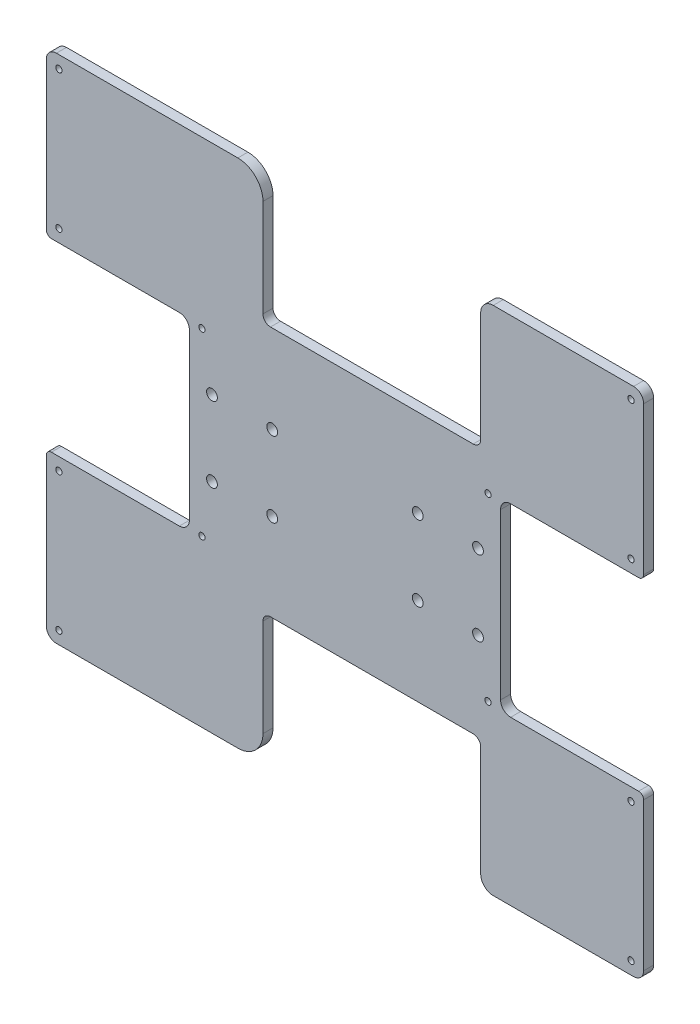
SolidWorks part; units mm, degrees
ref_plane "Front Plane" through (0, 0, 0) normal (0, 0, 1) x (1, 0, 0)
ref_plane "Top Plane" through (0, 0, 0) normal (0, 1, 0) x (1, 0, 0)
ref_plane "Right Plane" through (0, 0, 0) normal (1, 0, 0) x (0, 0, -1)
sketch "Sketch1" plane through (0, 0, 0) normal (0, 0, 1) x (1, 0, 0)
  line L0 (-141.718, 60) -> (-138.7986, 60) construction
  line L1 (-120, -43.5068) -> (-120, -41.8068) construction
  line L3 (-119, 97.8466) -> (-119, 38.8493)
  line L18 (-61.9992, -32.8493) -> (-61.9992, 32.8493)
  line L19 (-65.9992, 36.8493) -> (-117, 36.8493)
  line L20 (-29.6905, -50.0074) -> (51.0771, -50.0074)
  line L21 (-32.6905, -91.8466) -> (-32.6905, -53.0074)
  line L22 (-115, -101.8466) -> (-42.6905, -101.8466)
  line L23 (-65.9992, -36.8493) -> (-117, -36.8493)
  line L30 (-119, -97.8466) -> (-119, -38.8493)
  line L33 (-32.6905, 91.8466) -> (-32.6905, 53.0074)
  line L34 (-29.6905, 50.0074) -> (29.6905, 50.0074)
  line L35 (0, 0) -> (-20, 0) construction
  line L36 (0, 0) -> (0, 19.5721) construction
  line L40 (-115, 101.8466) -> (-42.6905, 101.8466)
  line L41 (115, 101.8466) -> (59.0771, 101.8466)
  line L43 (119, -97.8466) -> (119, -38.8493)
  line L44 (65.9992, -36.8493) -> (117, -36.8493)
  line L45 (115, -101.8466) -> (59.0771, -101.8466)
  line L47 (65.9992, 36.8493) -> (117, 36.8493)
  line L48 (61.9992, -32.8493) -> (61.9992, 32.8493)
  line L49 (119, 97.8466) -> (119, 38.8493)
  line L50 (29.6905, 50.0074) -> (51.0771, 50.0074)
  line L51 (54.0771, 53.0074) -> (54.0771, 96.8466)
  line L56 (54.0771, -53.0074) -> (54.0771, -96.8466)
  arc A3 (-119, 38.8493) -> (-117, 36.8493) centre (-117, 38.8493) ccw
  arc A27 (-32.6905, -53.0074) -> (-29.6905, -50.0074) centre (-29.6905, -53.0074) cw
  arc A31 (-42.6905, -101.8466) -> (-32.6905, -91.8466) centre (-42.6905, -91.8466) ccw
  arc A33 (-61.9992, -32.8493) -> (-65.9992, -36.8493) centre (-65.9992, -32.8493) cw
  arc A45 (-119, -38.8493) -> (-117, -36.8493) centre (-117, -38.8493) cw
  arc A50 (-61.9992, 32.8493) -> (-65.9992, 36.8493) centre (-65.9992, 32.8493) ccw
  arc A65 (-119, -97.8466) -> (-115, -101.8466) centre (-115, -97.8466) ccw
  arc A67 (-119, 97.8466) -> (-115, 101.8466) centre (-115, 97.8466) cw
  circle A71 centre (29, 15) radius 1.5
  circle A73 centre (53, 15) radius 1.5
  circle A75 centre (53, -15) radius 1.5
  circle A77 centre (29, -15) radius 1.5
  arc A82 (119, 97.8466) -> (115, 101.8466) centre (115, 97.8466) ccw
  arc A83 (119, -97.8466) -> (115, -101.8466) centre (115, -97.8466) cw
  arc A84 (61.9992, 32.8493) -> (65.9992, 36.8493) centre (65.9992, 32.8493) cw
  arc A85 (119, -38.8493) -> (117, -36.8493) centre (117, -38.8493) ccw
  arc A86 (61.9992, -32.8493) -> (65.9992, -36.8493) centre (65.9992, -32.8493) ccw
  arc A89 (119, 38.8493) -> (117, 36.8493) centre (117, 38.8493) cw
  arc A91 (51.0771, 50.0074) -> (54.0771, 53.0074) centre (51.0771, 53.0074) ccw
  arc A93 (54.0771, 96.8466) -> (59.0771, 101.8466) centre (59.0771, 96.8466) cw
  arc A95 (-42.6905, 101.8466) -> (-32.6905, 91.8466) centre (-42.6905, 91.8466) cw
  arc A106 (-32.6905, 53.0074) -> (-29.6905, 50.0074) centre (-29.6905, 53.0074) ccw
  arc A107 (51.0771, -50.0074) -> (54.0771, -53.0074) centre (51.0771, -53.0074) cw
  arc A108 (54.0771, -96.8466) -> (59.0771, -101.8466) centre (59.0771, -96.8466) ccw
  circle A109 centre (-114, 41.8493) radius 1
  circle A110 centre (-56.9992, 35.8493) radius 1
  circle A111 centre (-114, 96.8466) radius 1
  circle A112 centre (114, 96.8466) radius 1
  circle A113 centre (56.9992, 35.8493) radius 1
  circle A114 centre (-29, -15) radius 1.5
  circle A115 centre (-53, -15) radius 1.5
  circle A116 centre (-53, 15) radius 1.5
  circle A117 centre (-29, 15) radius 1.5
  circle A118 centre (114, 41.8493) radius 1
  circle A119 centre (114, -96.8466) radius 1
  circle A120 centre (114, -41.8493) radius 1
  circle A121 centre (56.9992, -35.8493) radius 1
  circle A122 centre (-56.9992, -35.8493) radius 1
  circle A123 centre (-114, -96.8466) radius 1
  circle A124 centre (-114, -41.8493) radius 1
  point P4 (0, -50.0074)
  point P7 (0, -50.0074)
  point P8 (61.9992, 0)
  point P65 (0, 50.0074)
  point P83 (0, 50.0074)
  point P111 (-61.9992, 0)
  dimension "D1" = 10
  dimension "D2" = 3
  dimension "D3" = 4
  dimension "D4" = 24
  dimension "D5" = 3
  dimension "D6" = 30
  dimension "D9" = 5
  dimension "D10" = 2
  dimension "D11" = 2
  dimension "D12" = 5
  dimension "D13" = 5
  dimension "D8" = 3
  dimension "D14" = 2
  dimension "D15" = 5
  dimension "D16" = 1
  dimension "D17" = 2
  dimension "D18" = 5
  dimension "D19" = 5
  dimension "D7" = 2
extrude "Boss-Extrude1" add sketch "Sketch1" along normal blind 4
hole_wizard "M4 Clearance Hole1" positions "3DSketch1" profile "Sketch2" hole size "M4" standard "ISO"
sketch3d "3DSketch1"
  line L0 (-53, 15, 4) -> (-53, 15, 0) construction
  line L1 (-29, 15, 4) -> (-29, 15, 0) construction
  line L2 (-53, -15, 4) -> (-53, -15, 0) construction
  line L3 (-29, -15, 4) -> (-29, -15, 0) construction
  line L4 (29, -15, 4) -> (29, -15, 0) construction
  line L5 (53, -15, 4) -> (53, -15, 0) construction
  line L6 (53, 15, 4) -> (53, 15, 0) construction
  line L7 (29, 15, 4) -> (29, 15, 0) construction
  point P0 (-53, 15, 4)
  point P4 (-29, 15, 4)
  point P8 (-53, -15, 4)
  point P12 (-29, -15, 4)
  point P16 (29, -15, 4)
  point P20 (53, -15, 4)
  point P24 (53, 15, 4)
  point P28 (29, 15, 4)
sketch "Sketch2" plane through (-53, 15, 4) normal (1, 0, 0) x (0, -1, 0)
  line L0 (0, 0) -> (0, 7.2919)
  line L1 (0, 7.2919) -> (2.15, 6)
  line L2 (2.15, 6) -> (2.15, 0)
  line L5 (2.15, 0) -> (0, 0)
  line L10 (0, 7.2919) -> (-2.15, 6) construction
  line L11 (0, -6.35) -> (0, 107.95) construction
  dimension "Hole Dia." = 4.3
  dimension "Hole Depth" = 6
  dimension "Drill Angle" = 118
hole_wizard "M3 Tapped Hole1" positions "3DSketch3" profile "Sketch4" tap size "M3" standard "ISO"
sketch3d "3DSketch3"
  line L0 (-114, -96.8466, 4) -> (-114, -96.8466, 0) construction
  line L1 (114, -96.8466, 4) -> (114, -96.8466, 0) construction
  line L2 (114, -41.8493, 4) -> (114, -41.8493, 0) construction
  line L3 (56.9992, -35.8493, 4) -> (56.9992, -35.8493, 0) construction
  line L4 (-56.9992, -35.8493, 4) -> (-56.9992, -35.8493, 0) construction
  line L5 (-114, -41.8493, 4) -> (-114, -41.8493, 0) construction
  line L6 (-114, 41.8493, 4) -> (-114, 41.8493, 0) construction
  line L7 (-56.9992, 35.8493, 4) -> (-56.9992, 35.8493, 0) construction
  line L8 (-114, 96.8466, 4) -> (-114, 96.8466, 0) construction
  line L9 (56.9992, 35.8493, 4) -> (56.9992, 35.8493, 0) construction
  line L10 (114, 41.8493, 4) -> (114, 41.8493, 0) construction
  line L11 (114, 96.8466, 4) -> (114, 96.8466, 0) construction
  point P0 (-114, -96.8466, 4)
  point P4 (114, -96.8466, 4)
  point P8 (114, -41.8493, 4)
  point P12 (56.9992, -35.8493, 4)
  point P16 (-56.9992, -35.8493, 4)
  point P21 (-114, -41.8493, 4)
  point P25 (-114, 41.8493, 4)
  point P29 (-56.9992, 35.8493, 4)
  point P33 (-114, 96.8466, 4)
  point P37 (56.9992, 35.8493, 4)
  point P41 (114, 41.8493, 4)
  point P45 (114, 96.8466, 4)
sketch "Sketch4" plane through (-114, -96.8466, 4) normal (1, 0, 0) x (0, -1, 0)
  line L0 (0, 0) -> (0, 8.2511)
  line L1 (0, 8.2511) -> (1.25, 7.5)
  line L2 (1.25, 7.5) -> (1.25, 0)
  line L5 (1.25, 0) -> (0, 0)
  line L10 (0, 8.2511) -> (-1.25, 7.5) construction
  line L11 (0, -6.35) -> (0, 107.95) construction
  dimension "Tap Drill Dia." = 2.5
  dimension "Tap Drill Depth" = 7.5
  dimension "Drill Angle" = 118
cosmetic thread "Hole Thread1" parameters "D1"=6, "D2"=3
cosmetic thread "Hole Thread2" parameters "D1"=6, "D2"=3
cosmetic thread "Hole Thread3" parameters "D1"=6, "D2"=3
cosmetic thread "Hole Thread4" parameters "D1"=6, "D2"=3
cosmetic thread "Hole Thread5" parameters "D1"=6, "D2"=3
cosmetic thread "Hole Thread6" parameters "D1"=6, "D2"=3
cosmetic thread "Hole Thread7" parameters "D1"=6, "D2"=3
cosmetic thread "Hole Thread8" parameters "D1"=6, "D2"=3
cosmetic thread "Hole Thread9" parameters "D1"=6, "D2"=3
cosmetic thread "Hole Thread10" parameters "D1"=6, "D2"=3
cosmetic thread "Hole Thread11" parameters "D1"=6, "D2"=3
cosmetic thread "Hole Thread12" parameters "D1"=6, "D2"=3
